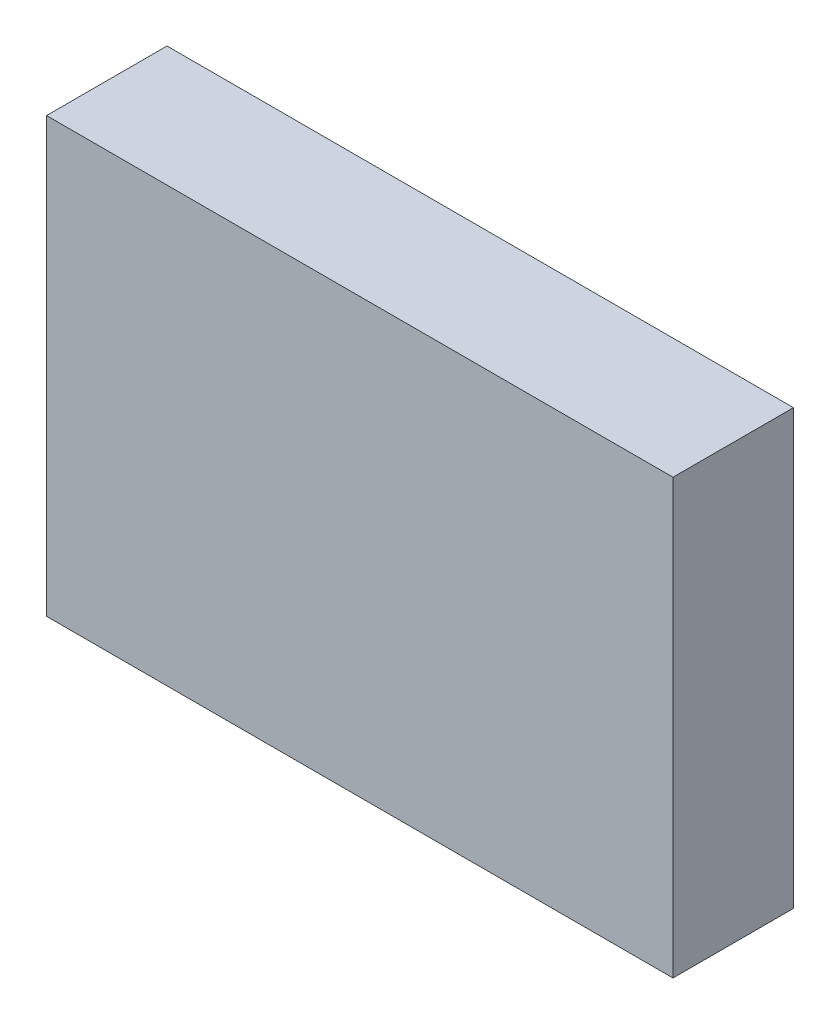
SolidWorks part; units mm, degrees
material "Epoxy, Unfilled"
ref_plane "Front Plane" through (0, 0, 0) normal (0, 0, 1) x (1, 0, 0)
ref_plane "Top Plane" through (0, 0, 0) normal (0, 1, 0) x (1, 0, 0)
ref_plane "Right Plane" through (0, 0, 0) normal (1, 0, 0) x (0, 0, -1)
sketch "Sketch1" plane through (0, 0, 0) normal (0, 0, 1) x (1, 0, 0)
  line L1 (-13, 9) -> (13, 9)
  line L2 (-13, 9) -> (-13, -9)
  line L3 (-13, -9) -> (13, -9)
  line L4 (13, 9) -> (13, -9)
  line L5 (-13, 9) -> (13, -9) construction
  line L6 (-13, -9) -> (13, 9) construction
  point P0 (0, 0)
  dimension "D1" = 18
  dimension "D2" = 26
extrude "Boss-Extrude1" add sketch "Sketch1" along normal blind 5
